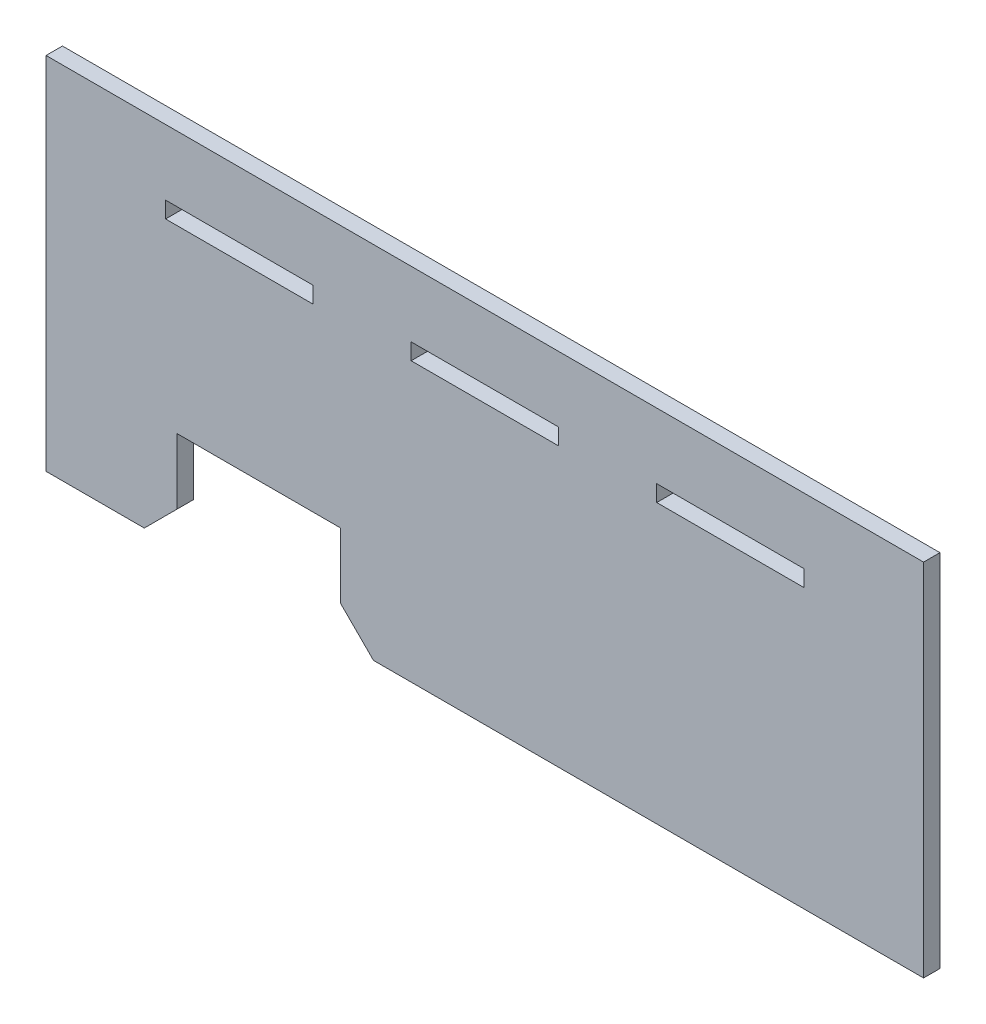
SolidWorks part; units mm, degrees
ref_plane "Plan de face" through (0, 0, 0) normal (0, 0, 1) x (1, 0, 0)
ref_plane "Plan de dessus" through (0, 0, 0) normal (0, 1, 0) x (1, 0, 0)
ref_plane "Plan de droite" through (0, 0, 0) normal (1, 0, 0) x (0, 0, -1)
sketch "Esquisse1" plane through (0, 0, 0) normal (0, 0, 1) x (1, 0, 0)
  line L0 (0, 220) -> (536, 220)
  line L1 (0, 0) -> (536, 0) construction
  line L2 (0, 0) -> (0, 220)
  line L3 (0, 180) -> (536, 180) construction
  line L4 (536, 0) -> (536, 220)
  line L5 (536, 175) -> (0, 175) construction
  line L6 (0, 170) -> (536, 170) construction
  line L7 (313, 170) -> (223, 170) construction
  line L8 (163, 170) -> (73, 170)
  line L9 (163, 180) -> (163, 170)
  line L10 (0, 0) -> (80, 0)
  line L11 (223, 180) -> (223, 170)
  line L12 (80, 0) -> (80, 60)
  line L13 (313, 180) -> (313, 170)
  line L14 (80, 60) -> (180, 60)
  line L15 (373, 180) -> (373, 170)
  line L16 (268, 170) -> (268, 180) construction
  line L17 (0, 0) -> (35, -60.6218) construction
  line L18 (463, 170) -> (373, 170)
  line L19 (463, 180) -> (463, 170)
  line L20 (373, 180) -> (463, 180)
  line L21 (313, 180) -> (223, 180)
  line L22 (180, 60) -> (180, 0)
  line L23 (73, 180) -> (73, 170)
  line L24 (180, 0) -> (200, 0)
  line L26 (40, -69.282) -> (80, -69.282) construction
  line L27 (200, 0) -> (80, -69.282) construction
  line L28 (200, 0) -> (436, 0)
  line L29 (436, 0) -> (444.0385, -30) construction
  line L30 (444.0385, -30) -> (484.0385, -30) construction
  line L31 (444.0385, -30) -> (449.3975, -50) construction
  line L32 (60, -69.282) -> (60, 0) construction
  line L33 (464.0385, -30) -> (464.0385, 0) construction
  line L34 (40, -69.282) -> (50, -86.6025) construction
  line L35 (80, -69.282) -> (75.9808, -71.6025) construction
  line L36 (40, -69.282) -> (40, 0) construction
  line L37 (536, 0) -> (484.0385, -30) construction
  line L38 (484.0385, -30) -> (449.3975, -50) construction
  line L39 (484.0385, -30) -> (484.0385, 0) construction
  line L40 (436, 0) -> (536, 0)
  line L41 (200, 0) -> (0, 0) construction
  line L42 (223, 170) -> (313, 170)
  line L43 (163, 180) -> (73, 180)
  circle A0 centre (60, -40) radius 15 construction
  arc A1 (35, -60.6218) -> (75.9808, -71.6025) centre (60.9808, -45.6218) ccw construction
  circle A2 centre (464.0385, -20) radius 10.125 construction
  dimension "D13" = 30
  dimension "D19" = 30
  dimension "D22" = 20.25
  dimension "D1" = 10
  dimension "D2" = 5
  dimension "D3" = 40
  dimension "D4" = 220
  dimension "D5" = 536
  dimension "D6" = 60
  dimension "D7" = 90
  dimension "D8" = 60
  dimension "D9" = 60
  dimension "D10" = 100
  dimension "D11" = 90
  dimension "D12" = 90
  dimension "D14" = 40
  dimension "D15" = 60
  dimension "D16" = 30
  dimension "D17" = 20
  dimension "D18" = 40
  dimension "D20" = 30
  dimension "D21" = 75
  dimension "D23" = 20
  dimension "D24" = 30
  dimension "D25" = 20
  dimension "D26" = 80
extrude "Boss.-Extru.1" add sketch "Esquisse1" along normal blind 10
chamfer "Chanfrein1" distance 20 angle 45 2 edges at (80, 0, 5) (180, 0, 5)
